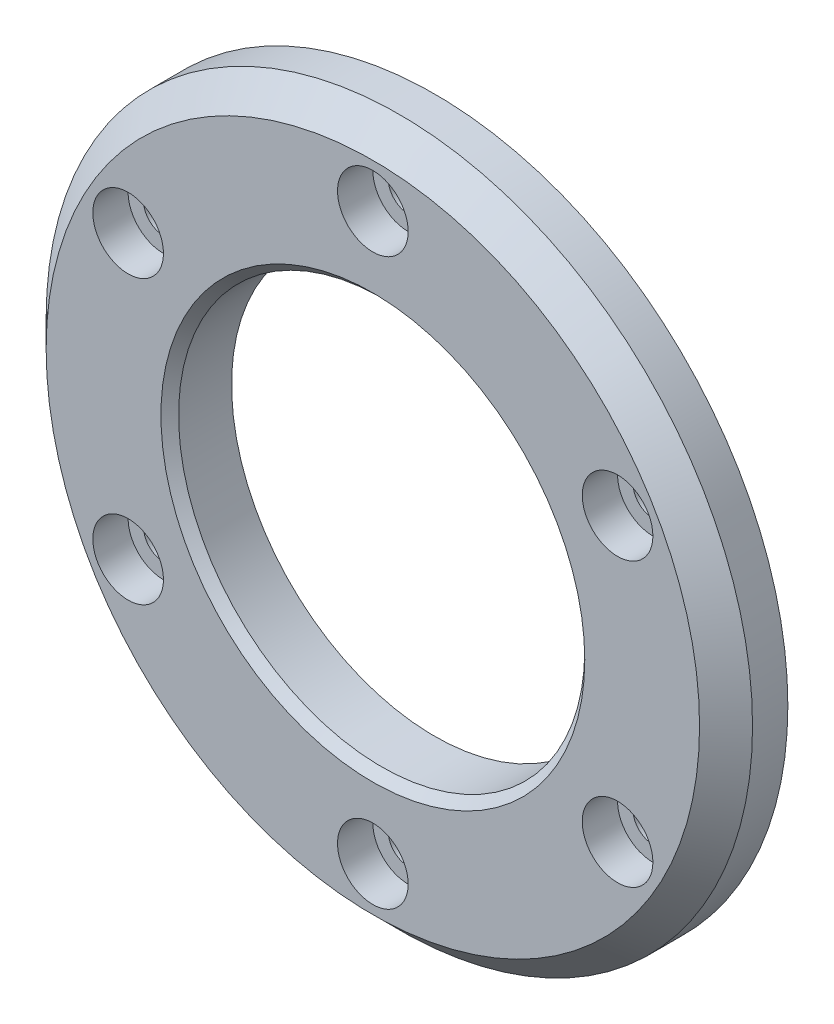
SolidWorks part; units mm, degrees
ref_plane "正面" through (0, 0, 0) normal (0, 0, 1) x (1, 0, 0)
ref_plane "平面" through (0, 0, 0) normal (0, 1, 0) x (1, 0, 0)
ref_plane "右側面" through (0, 0, 0) normal (1, 0, 0) x (0, 0, -1)
sketch "ｽｹｯﾁ1" plane through (0, 0, 0) normal (0, 0, 1) x (1, 0, 0)
  arc B0 (-37.6198, -15) -> (37.6198, -15) centre (0, 0) ccw
  arc B1 (40, 0) -> (-40, 0) centre (0, 0) ccw
  circle B2 centre (0, 0) radius 26
  circle B3 centre (0, -32) radius 1.5
  circle B4 centre (27.7128, -16) radius 1.5
  circle B5 centre (27.7128, 16) radius 1.5
  circle B6 centre (-27.7128, -16) radius 1.5
  circle B7 centre (-27.7128, 16) radius 1.5
  circle B8 centre (0, 32) radius 1.5
sketch_block_instance "ﾌﾞﾛｯｸ1-1"
sketch_block "ﾌﾞﾛｯｸ1"
sketch "ｽｹｯﾁ2" plane through (0, 0, 0) normal (0, 0, 1) x (1, 0, 0)
  circle A0 centre (0, 0) radius 40
  circle A1 centre (0, 32) radius 2.25
  circle A2 centre (0, 0) radius 23
  circle A3 centre (0, 0) radius 26 construction
  circle A4 centre (-27.7128, 16) radius 2.25
  circle A5 centre (-27.7128, -16) radius 2.25
  circle A6 centre (0, -32) radius 2.25
  circle A7 centre (27.7128, -16) radius 2.25
  circle A8 centre (27.7128, 16) radius 2.25
  point P20 (-27.7128, 16)
  point P21 (-27.7128, -16)
  point P24 (0, -32)
  point P26 (27.7128, -16)
  point P28 (27.7128, 16)
  dimension "D1" = 4.5
  dimension "D2" = 3
extrude "ﾎﾞｽ - 押し出し1" add sketch "ｽｹｯﾁ2" along normal blind 3
sketch "ｽｹｯﾁ3" plane through (0, 0, 3) normal (0, 0, 1) x (1, 0, 0)
  circle A0 centre (0, 32) radius 4
  circle A1 centre (-27.7128, 16) radius 4
  circle A2 centre (-27.7128, -16) radius 4
  circle A3 centre (0, -32) radius 4
  circle A4 centre (27.7128, -16) radius 4
  circle A5 centre (27.7128, 16) radius 4
  circle A6 centre (0, 0) radius 23 construction
  circle A8 centre (0, 0) radius 23
  circle A9 centre (0, 0) radius 40 construction
  circle A10 centre (0, 0) radius 40
  point P13 (-27.7128, 16)
  point P14 (-27.7128, -16)
  point P17 (0, -32)
  point P19 (27.7128, -16)
  point P21 (0, 0)
  point P22 (27.7128, 16)
  dimension "D1" = 8
extrude "ﾎﾞｽ - 押し出し2" add sketch "ｽｹｯﾁ3" along normal blind 4
chamfer "面取り1" distance 3 angle 45 1 edges at (40, 0, 7)
chamfer "面取り2" distance 1 angle 45 1 edges at (23, 0, 7)
